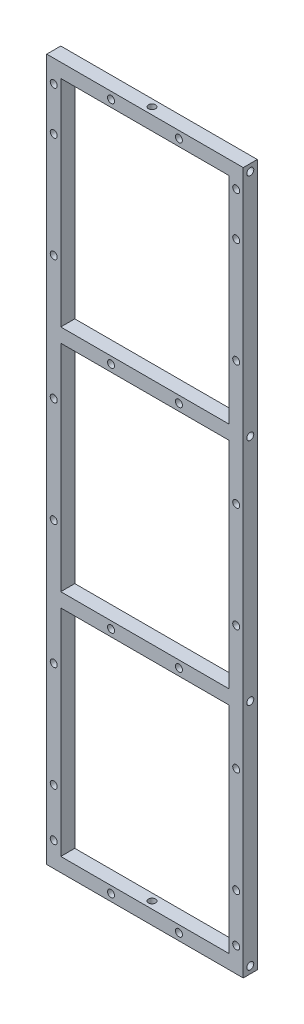
SolidWorks part; units mm, degrees
ref_plane "Front Plane" through (0, 0, 0) normal (0, 0, 1) x (1, 0, 0)
ref_plane "Top Plane" through (0, 0, 0) normal (0, 1, 0) x (1, 0, 0)
ref_plane "Right Plane" through (0, 0, 0) normal (1, 0, 0) x (0, 0, -1)
sketch "Sketch1" plane through (0, 0, 0) normal (0, 0, 1) x (1, 0, 0)
  line L0 (36, 144) -> (36, 52)
  line L9 (-42, -150) -> (42, -150)
  line L10 (-42, -150) -> (-42, 150)
  line L11 (-42, 150) -> (42, 150)
  line L12 (42, -150) -> (42, 150)
  line L15 (-36, -144) -> (36, -144)
  line L16 (-36, -144) -> (-36, -52)
  line L17 (-36, 144) -> (36, 144)
  line L21 (-36, 52) -> (36, 52)
  line L23 (-36, 46) -> (36, 46)
  line L25 (-36, -46) -> (36, -46)
  line L27 (-36, -52) -> (36, -52)
  line L33 (36, 46) -> (36, -46)
  line L34 (-36, 52) -> (-36, 144)
  line L35 (-36, -46) -> (-36, 46)
  line L36 (36, -52) -> (36, -144)
  point P0 (0, 0)
  point P4 (0, -46)
  point P6 (0, 0)
  point P20 (0, 0)
  point P21 (0, -150)
  dimension "D1" = 84
  dimension "D2" = 300
  dimension "D3" = 72
  dimension "D4" = 288
  dimension "D5" = 6
  dimension "D6" = 92
  dimension "D7" = 6
  dimension "D8" = 92
  dimension "D9" = 6
  dimension "D10" = 6
  dimension "D11" = 92
extrude "Boss-Extrude1" add sketch "Sketch1" along normal blind 6
sketch "Sketch2" plane through (42, 0, 0) normal (1, 0, 0) x (0, 0, -1)
  line L0 (-6, 150) -> (0, 150) construction
  circle A0 centre (-3, 147) radius 1.5
  circle A1 centre (-3, 49) radius 1.5
  circle A2 centre (-3, -49) radius 1.5
  circle A3 centre (-3, -147) radius 1.5
  dimension "D1" = 3
  dimension "D2" = 4
extrude "Cut-Extrude1" cut sketch "Sketch2" against normal blind 10
mirror "Mirror1" about plane through (0, 0, 0) normal (1, 0, 0) of "Cut-Extrude1"
sketch "Sketch3" plane through (0, 0, 6) normal (0, 0, 1) x (1, 0, 0)
  line L0 (-42, 150) -> (42, 150) construction
  line L1 (-42, -150) -> (-42, 150) construction
  circle A0 centre (-39, 140.5) radius 1.5
  circle A1 centre (39, 140.5) radius 1.5
  circle A2 centre (39, -139.5) radius 1.5
  circle A3 centre (-39, -139.5) radius 1.5
  dimension "D1" = 9.5
  dimension "D2" = 3
  dimension "D3" = 2
  dimension "D4" = 2
extrude "Cut-Extrude2" cut sketch "Sketch3" against normal blind 10
sketch "Sketch4" plane through (0, 0, 6) normal (0, 0, 1) x (1, 0, 0)
  line L0 (-42, -150) -> (-42, 150) construction
  line L1 (42, -150) -> (42, 150) construction
  line L2 (-42, 150) -> (42, 150) construction
  circle A0 centre (-14.5, 147) radius 1.5
  circle A1 centre (14.5, 147) radius 1.5
  circle A2 centre (14.5, 49) radius 1.5
  circle A3 centre (-14.5, 49) radius 1.5
  circle A4 centre (14.5, -49) radius 1.5
  circle A5 centre (-14.5, -49) radius 1.5
  circle A6 centre (14.5, -147) radius 1.5
  circle A7 centre (-14.5, -147) radius 1.5
  circle A8 centre (-39, 122) radius 1.5
  circle A9 centre (-39, 77) radius 1.5
  circle A10 centre (39, 122) radius 1.5
  circle A11 centre (39, 77) radius 1.5
  circle A12 centre (39, 24) radius 1.5
  circle A13 centre (39, -21) radius 1.5
  circle A14 centre (39, -74) radius 1.5
  circle A15 centre (39, -119) radius 1.5
  circle A16 centre (-39, 24) radius 1.5
  circle A17 centre (-39, -21) radius 1.5
  circle A18 centre (-39, -74) radius 1.5
  circle A19 centre (-39, -119) radius 1.5
  dimension "D1" = 27.5
  dimension "D4" = 45
  dimension "D7" = 2
  dimension "D2" = 27.5
  dimension "D3" = 4
  dimension "D5" = 28
  dimension "D6" = 28
  dimension "D9" = 3
  dimension "D8" = 3
extrude "Cut-Extrude3" cut sketch "Sketch4" against normal blind 10
sketch "Sketch5" plane through (0, 150, 0) normal (0, 1, 0) x (1, 0, 0)
  line L0 (42, -6) -> (-42, -6) construction
  circle A0 centre (0, -3) radius 1.5
  point P5 (0, -6)
  dimension "D1" = 3
extrude "Cut-Extrude4" cut sketch "Sketch5" against normal blind 10
mirror "Mirror2" about plane through (0, 0, 0) normal (0, 1, 0) of "Cut-Extrude4"
